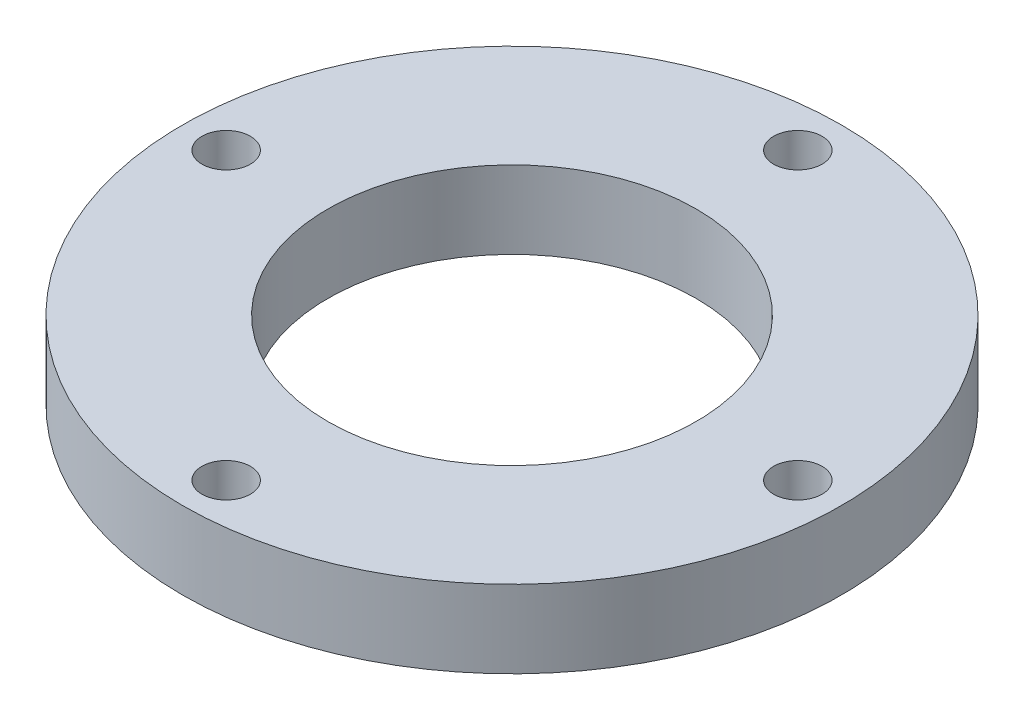
SolidWorks part; units mm, degrees
ref_plane "Спереди" through (0, 0, 0) normal (0, 0, 1) x (1, 0, 0)
ref_plane "Сверху" through (0, 0, 0) normal (0, 1, 0) x (1, 0, 0)
ref_plane "Справа" through (0, 0, 0) normal (1, 0, 0) x (0, 0, -1)
sketch "Эскиз1" plane through (0, 0, 0) normal (0, 1, 0) x (1, 0, 0)
  circle A0 centre (0, 0) radius 34
  circle A1 centre (0, 0) radius 19
extrude "Вытянуть1" add sketch "Эскиз1" along normal blind 8
sketch "Эскиз2" plane through (0, 8, 0) normal (0, 1, 0) x (1, 0, 0)
  circle A0 centre (0, 29.4896) radius 2.5
  circle A1 centre (29.4896, 0) radius 2.5
  circle A2 centre (0, -29.4896) radius 2.5
  circle A3 centre (-29.4896, 0) radius 2.5
extrude "Вырез-Вытянуть1" cut sketch "Эскиз2" against normal through all
